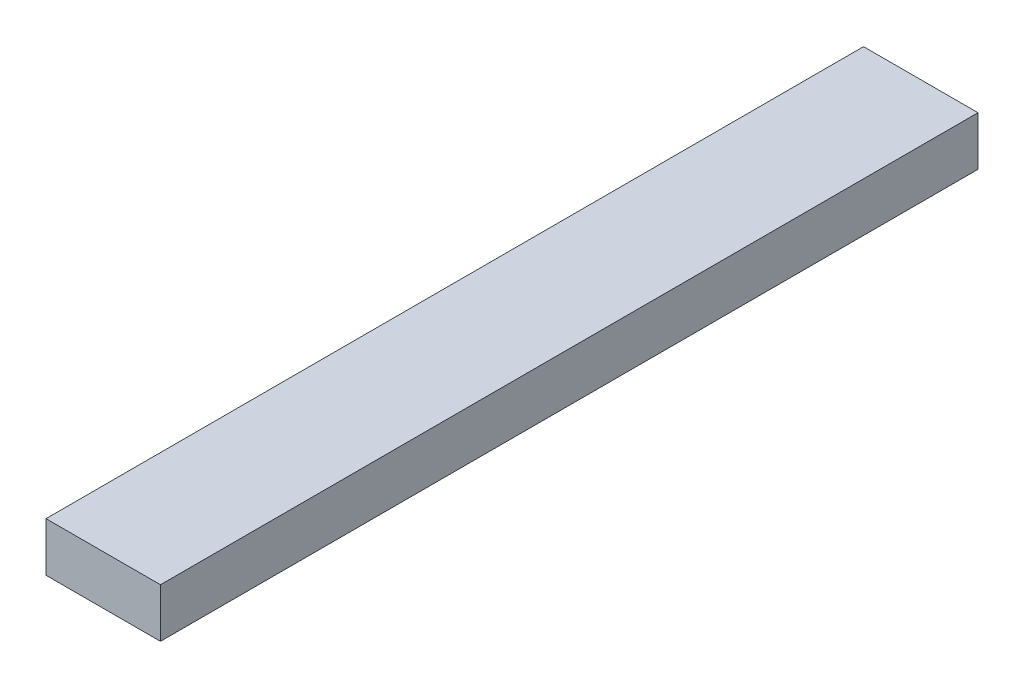
SolidWorks part; units mm, degrees
material "Pine"
ref_plane "Front Plane" through (0, 0, 0) normal (0, 0, 1) x (1, 0, 0)
ref_plane "Top Plane" through (0, 0, 0) normal (0, 1, 0) x (1, 0, 0)
ref_plane "Right Plane" through (0, 0, 0) normal (1, 0, 0) x (0, 0, -1)
sketch "Sketch1" plane through (0, 0, 0) normal (0, 0, 1) x (1, 0, 0)
  line L1 (0, 0) -> (88.9, 0)
  line L2 (0, 0) -> (0, -38.1)
  line L3 (0, -38.1) -> (88.9, -38.1)
  line L4 (88.9, 0) -> (88.9, -38.1)
  dimension "D1" = 88.9
  dimension "D2" = 38.1
extrude "Boss-Extrude1" add sketch "Sketch1" along normal blind 635
equation "\"D1@Boss-Extrude1\"=\"BottomSupportLength\""
equation "\"TableFrontWidth\"=64"
equation "\"TableSideWidth\"=28"
equation "\"LegWidth\"=3.5"
equation "\"LegHeight\"=32"
equation "\"LegDistToBottomStretcher\"=7"
equation "\"BottomStretcherLength\"=\"TableFrontWidth\""
equation "\"SideStretcherLength\"=\"TableSideWidth\"-3"
equation "\"BottomSupportLength\"=\"TableSideWidth\"-3"
equation "\"BottomPlywoodFrontDim\"=\"TableFrontWidth\"-\"LegWidth\"*2-3"
equation "\"BottomPlywoodSideDim\"=\"BottomSupportLength\""
equation "\"TotalBottomSupports\"=4"
equation "\"TotalBottomSupportsLessOne\"=\"TotalBottomSupports\"-1"
equation "\"TotalTopSupports\"=5"
equation "\"TotalTopSupportsLessOne\"=\"TotalTopSupports\"-1"
equation "\"TopSupportSpread\"=\"TableFrontWidth\"-1.5"
equation "\"DistBetweenTopSupports\"=\"TopSupportSpread\"/\"TotalTopSupportsLessOne\""
equation "\"BottomSupportSpread\"= \"BottomPlywoodFrontDim\" - 1.5"
equation "\"DistBetweenBottomSupports\"=\"BottomSupportSpread\"/\"TotalBottomSupportsLessOne\""
equation "\"OverhangFrontDim\"=4"
equation "\"OverhangSideDim\"=4"
